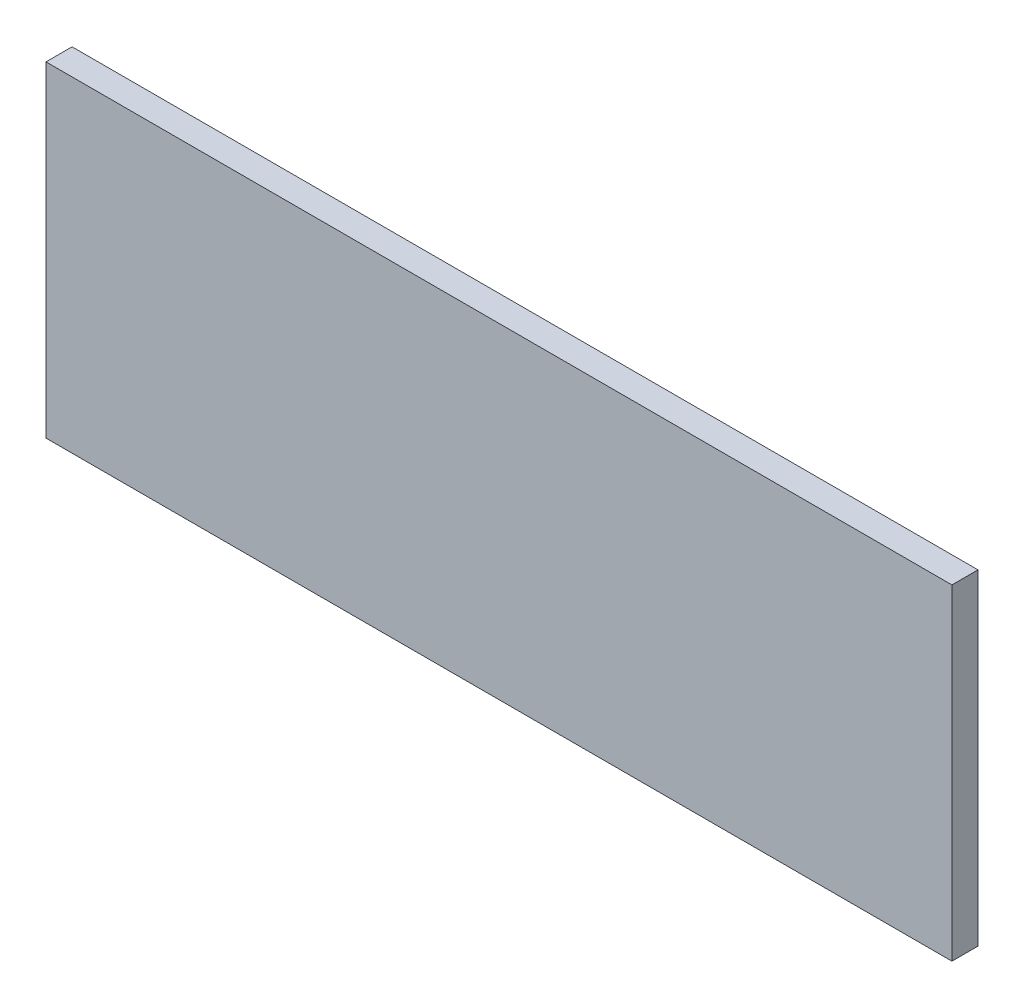
SolidWorks part; units mm, degrees
ref_plane "Alzado" through (0, 0, 0) normal (0, 0, 1) x (1, 0, 0)
ref_plane "Planta" through (0, 0, 0) normal (0, 1, 0) x (1, 0, 0)
ref_plane "Vista lateral" through (0, 0, 0) normal (1, 0, 0) x (0, 0, -1)
sketch "Croquis1" plane through (0, 0, 0) normal (0, 0, 1) x (1, 0, 0)
  line L1 (0, 0) -> (139, 0)
  line L2 (0, 0) -> (0, -50)
  line L3 (0, -50) -> (139, -50)
  line L4 (139, 0) -> (139, -50)
  dimension "D1" = 139
  dimension "D2" = 50
extrude "Saliente-Extruir1" add sketch "Croquis1" along normal blind 4
